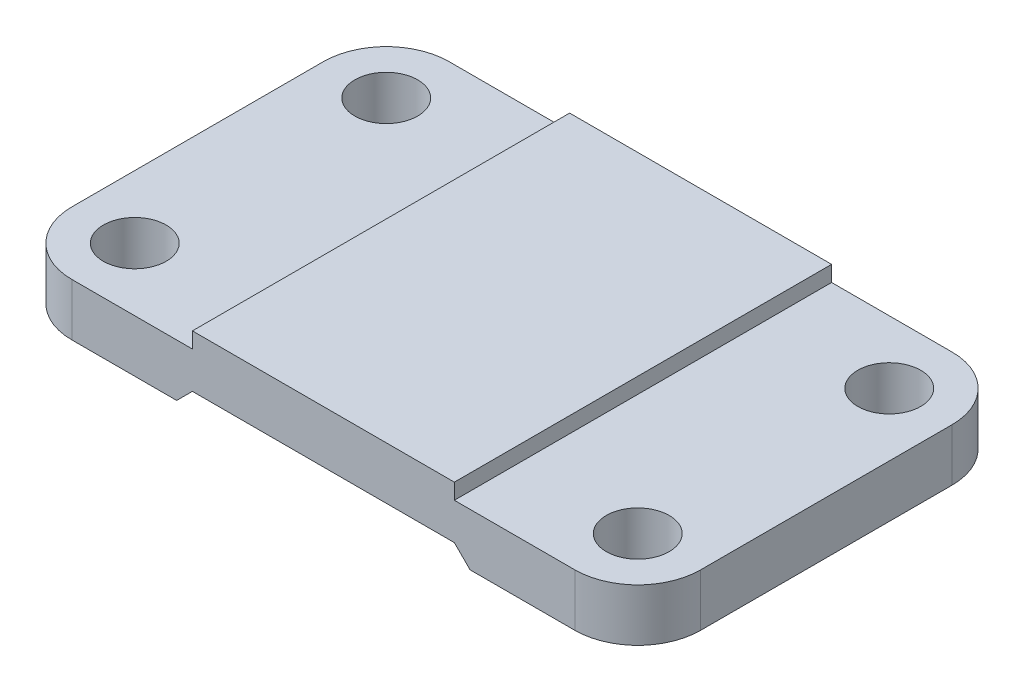
SolidWorks part; units mm, degrees
ref_plane "Front Plane" through (0, 0, 0) normal (0, 0, 1) x (1, 0, 0)
ref_plane "Top Plane" through (0, 0, 0) normal (0, 1, 0) x (1, 0, 0)
ref_plane "Right Plane" through (0, 0, 0) normal (1, 0, 0) x (0, 0, -1)
sketch "Sketch3" plane through (0, 0, 0) normal (0, 1, 0) x (1, 0, 0)
  line L1 (48, -36) -> (-48, -36)
  line L2 (60, -24) -> (60, 24)
  line L3 (48, 36) -> (-48, 36)
  line L4 (-60, -24) -> (-60, 24)
  arc A0 (-48, 36) -> (-60, 24) centre (-48, 24) ccw
  arc A1 (-48, -36) -> (-60, -24) centre (-48, -24) cw
  arc A2 (48, -36) -> (60, -24) centre (48, -24) ccw
  arc A3 (60, 24) -> (48, 36) centre (48, 24) ccw
  circle A4 centre (-48, 24) radius 6
  circle A5 centre (-48, -24) radius 6
  circle A6 centre (48, -24) radius 6
  circle A7 centre (48, 24) radius 6
  point P0 (0, 0)
  dimension "D1" = 12
  dimension "D2" = 12
  dimension "D3" = 60
  dimension "D4" = 60
  dimension "D5" = 36
  dimension "D6" = 36
extrude "Boss-Extrude1" add sketch "Sketch3" along normal blind 10
sketch "Sketch4" plane through (0, 10, 0) normal (0, 1, 0) x (1, 0, 0)
  line L0 (-60, 24) -> (-60, -24) construction
  line L1 (-25, 36) -> (25, 36)
  line L2 (-25, 36) -> (-25, -36)
  line L3 (-25, -36) -> (25, -36)
  line L4 (25, 36) -> (25, -36)
  line L5 (-48, -36) -> (48, -36) construction
  point P0 (0, 0)
  dimension "D1" = 35
  dimension "D2" = 85
  dimension "D3" = 72
extrude "Boss-Extrude2" add sketch "Sketch4" along normal blind 3
sketch "Sketch5" plane through (0, 0, 36) normal (0, 0, 1) x (1, 0, 0)
  line L0 (28, 0) -> (-28, 0)
  line L1 (-48, 0) -> (48, 0) construction
  line L2 (-28, 0) -> (0, 0)
  line L3 (-25, 3) -> (25, 3)
  line L4 (-25, 3) -> (-28, 0)
  line L5 (48, 10) -> (48, 0) construction
  line L6 (25, 3) -> (28, 0)
  line M6 (-48, 0) -> (48, 0)
  dimension "D1" = 20
  dimension "D2" = 23
  dimension "D3" = 48
extrude "Cut-Extrude1" cut sketch "Sketch5" against normal through all contours L6 L3 L4 L0 M6
